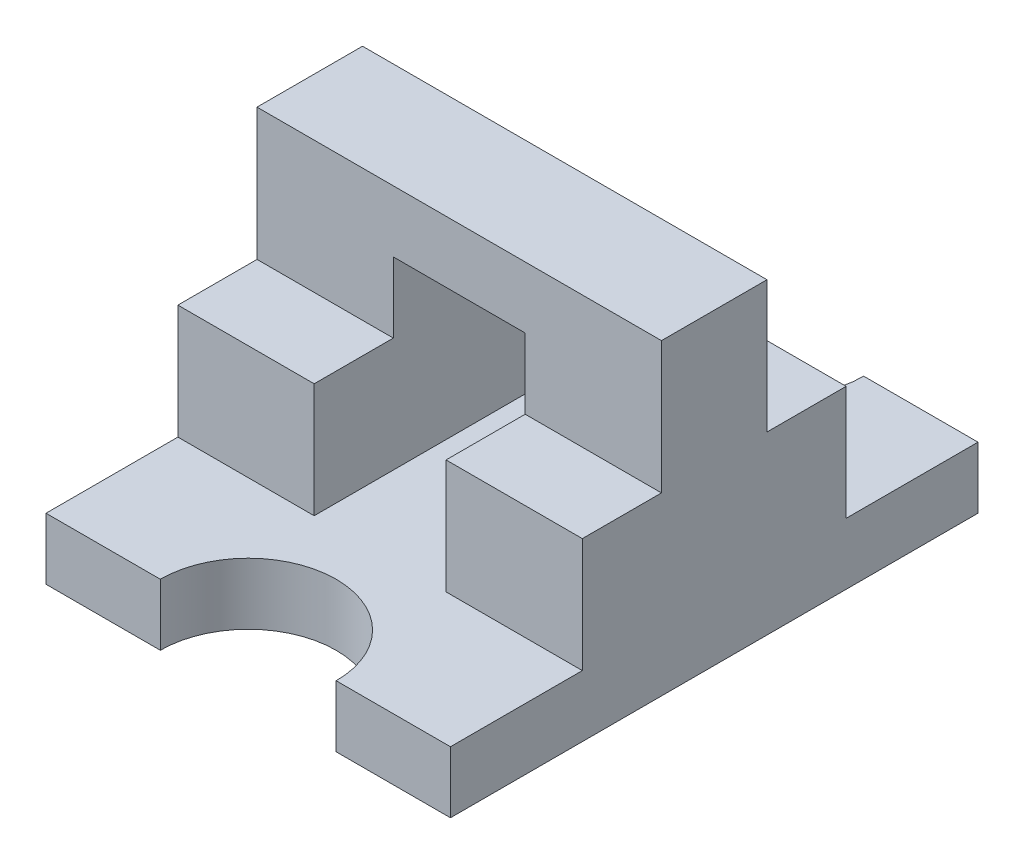
SolidWorks part; units mm, degrees
ref_plane "Front Plane" through (0, 0, 0) normal (0, 0, 1) x (1, 0, 0)
ref_plane "Top Plane" through (0, 0, 0) normal (0, 1, 0) x (1, 0, 0)
ref_plane "Right Plane" through (0, 0, 0) normal (1, 0, 0) x (0, 0, -1)
sketch "Sketch1" plane through (0, 0, 0) normal (1, 0, 0) x (0, 0, -1)
  line L0 (0, 0) -> (60, 0)
  line L1 (60, 0) -> (60, 7)
  line L2 (60, 7) -> (45, 7)
  line L3 (45, 7) -> (45, 20)
  line L4 (45, 20) -> (36, 20)
  line L5 (36, 20) -> (36, 35)
  line L6 (36, 35) -> (24, 35)
  line L7 (24, 35) -> (24, 20)
  line L8 (24, 20) -> (15, 20)
  line L9 (15, 20) -> (15, 7)
  line L10 (15, 7) -> (0, 7)
  line L11 (0, 7) -> (0, 0)
  line L12 (24, 28) -> (36, 28)
  dimension "D1" = 60
  dimension "D2" = 7
  dimension "D3" = 20
  dimension "D4" = 7
  dimension "D5" = 20
  dimension "D6" = 28
  dimension "D7" = 35
  dimension "D8" = 15
  dimension "D9" = 15
  dimension "D10" = 24
  dimension "D11" = 24
extrude "Boss-Extrude1" add sketch "Sketch1" along normal blind 46 contours L7 L12 L5 L6 | L12 L7 L8 L9 L10 L11 L0 L1 L2 L3 L4 L5
sketch "Sketch2" plane through (0, 0, 0) normal (0, 1, 0) x (1, 0, 0)
  line L0 (0, 15) -> (0, 0) construction
  line L1 (0, 0) -> (46, 0) construction
  line L2 (46, 0) -> (46, 15) construction
  line L3 (46, 15) -> (0, 15) construction
  line L4 (0, 60) -> (0, 45) construction
  line L5 (0, 45) -> (46, 45) construction
  line L6 (46, 45) -> (46, 60) construction
  line L7 (46, 60) -> (0, 60) construction
  line L8 (0, 15) -> (0, 0)
  line L9 (0, 0) -> (46, 0)
  line L10 (46, 0) -> (46, 15)
  line L11 (46, 15) -> (0, 15)
  line L12 (0, 60) -> (0, 45)
  line L13 (0, 45) -> (46, 45)
  line L14 (46, 45) -> (46, 60)
  line L15 (46, 60) -> (0, 60)
  circle A0 centre (23, 60) radius 10
  circle A1 centre (23, 0) radius 10
  dimension "D1" = 20
  dimension "D2" = 20
extrude "Cut-Extrude2" cut sketch "Sketch2" against normal blind 46 and the other way blind 46 contours L9 A1 | L15 A0
sketch "Sketch6" plane through (0, 0, 0) normal (0, 0, 1) x (1, 0, 0)
  line L0 (15.5, 7) -> (15.5, 28)
  line L1 (33, 7) -> (13, 7) construction
  line L2 (15.5, 28) -> (30.5, 28)
  line L3 (30.5, 28) -> (30.5, 7)
  line L4 (46, 7) -> (0, 7) construction
  line L5 (30.5, 7) -> (15.5, 7)
  line L6 (0, 35) -> (0, 20) construction
  line L7 (46, 35) -> (46, 20) construction
  line L8 (13, 0) -> (33, 0) construction
  dimension "D1" = 15.5
  dimension "D2" = 15.5
  dimension "D3" = 28
extrude "Cut-Extrude3" cut sketch "Sketch6" against normal blind 60 contours L5 L0 L2 L3
